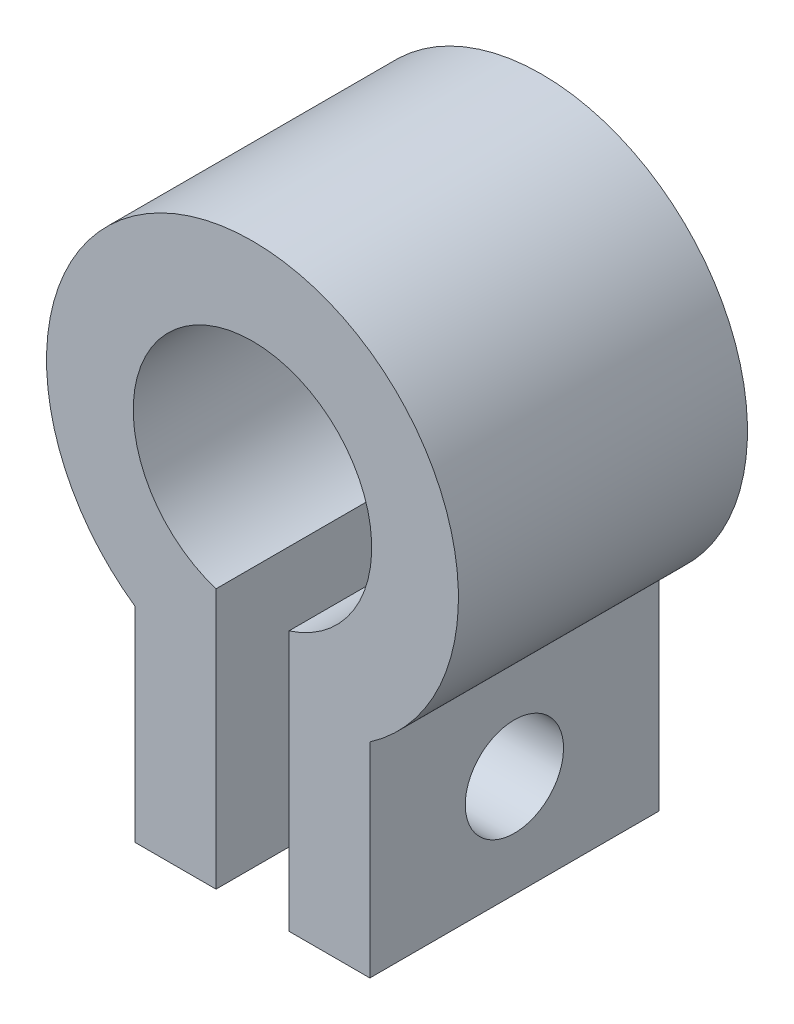
SolidWorks part; units mm, degrees
ref_plane "Front Plane" through (0, 0, 0) normal (0, 0, 1) x (1, 0, 0)
ref_plane "Top Plane" through (0, 0, 0) normal (0, 1, 0) x (1, 0, 0)
ref_plane "Right Plane" through (0, 0, 0) normal (1, 0, 0) x (0, 0, -1)
sketch "Sketch1" plane through (0, 0, 0) normal (0, 0, 1) x (1, 0, 0)
  line L0 (0, -7.125) -> (0, 7.125) construction
  line L1 (1.2612, -10.9741) -> (1.2612, 13.6006) construction
  line L2 (-1.2612, -10.9741) -> (-1.2612, 13.6006) construction
  line L3 (1.2612, -12.9275) -> (4.0612, -12.9275)
  line L4 (-1.2612, -3.9275) -> (-4.0612, -3.9275)
  line L5 (-1.2612, -3.9275) -> (-1.2612, -12.9275)
  line L6 (-1.2612, -12.9275) -> (-4.0612, -12.9275)
  line L7 (-4.0612, -3.9275) -> (-4.0612, -12.9275)
  line L8 (4.0612, -3.9275) -> (4.0612, -12.9275)
  line L9 (1.2612, -3.9275) -> (4.0612, -3.9275)
  line L10 (1.2612, -3.9275) -> (1.2612, -12.9275)
  circle A0 centre (0, 0) radius 4.125
  circle A1 centre (0, 0) radius 7.125
  point P14 (-3.7386, -11.2369)
  dimension "D1" = 8.25
  dimension "D2" = 3
  dimension "D3" = 2.8
  dimension "D4" = 9
extrude "Boss-Extrude1" add sketch "Sketch1" along normal blind 10 contours L8 A1 L7 L4 A0 L9 | L7 A1 L5 L4 | L10 A1 L8 L9 | A1 L10 L3 L8 | A1 L7 L6 L5
sketch "Sketch2" plane through (-4.0612, 0, 0) normal (-1, 0, 0) x (0, 0, 1)
  line L0 (10, -12.9275) -> (0, -5.8542) construction
  line L1 (10, -5.8542) -> (0, -12.9275) construction
  circle A0 centre (5, -9.3908) radius 1.7
  point P10 (6.1304, -7.8174)
  point P11 (5, -9.3908)
  dimension "D1" = 3.4
extrude "Cut-Extrude1" cut sketch "Sketch2" against normal through all
